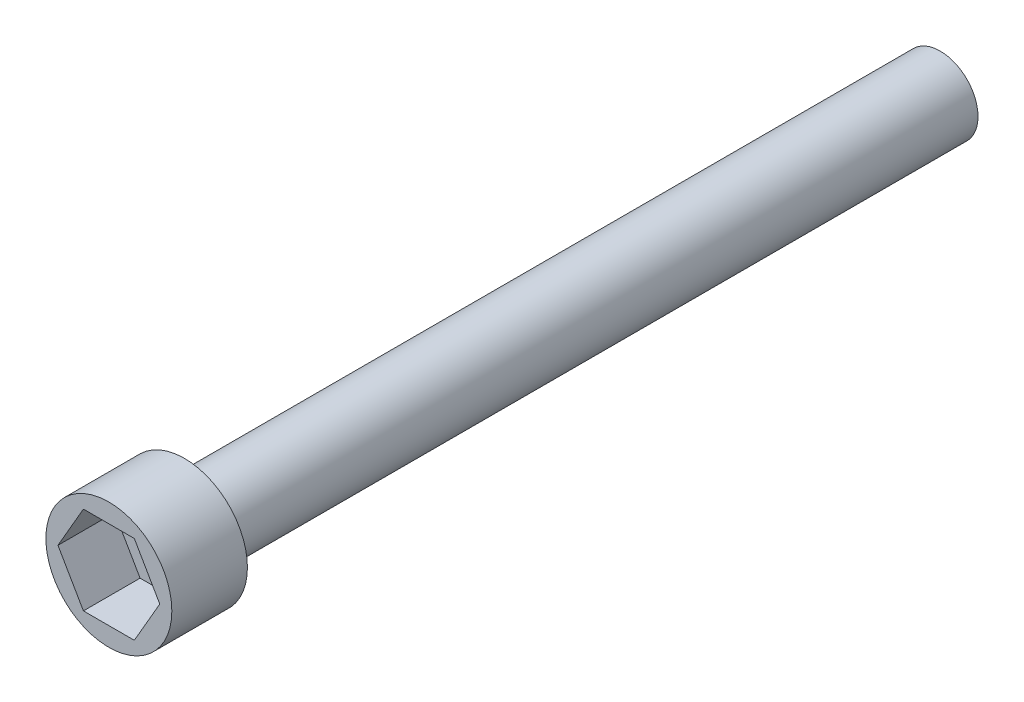
SolidWorks part; units mm, degrees
ref_plane "Plan de face" through (0, 0, 0) normal (0, 0, 1) x (1, 0, 0)
ref_plane "Plan de dessus" through (0, 0, 0) normal (0, 1, 0) x (1, 0, 0)
ref_plane "Plan de droite" through (0, 0, 0) normal (1, 0, 0) x (0, 0, -1)
sketch "Esquisse1" plane through (0, 0, 0) normal (0, 0, 1) x (1, 0, 0)
  circle A0 centre (0, 0) radius 3
  dimension "D1" = 6
extrude "Boss.-Extru.1" add sketch "Esquisse1" along normal blind 60
sketch "Esquisse2" plane through (0, 0, 60) normal (0, 0, 1) x (1, 0, 0)
  circle A0 centre (0, 0) radius 5
  dimension "D1" = 10
extrude "Boss.-Extru.2" add sketch "Esquisse2" along normal blind 6
sketch "Esquisse3" plane through (0, 0, 66) normal (0, 0, 1) x (1, 0, 0)
  line L1 (4.0415, 0) -> (2.0207, 3.5)
  line L2 (2.0207, 3.5) -> (-2.0207, 3.5)
  line L3 (-2.0207, 3.5) -> (-4.0415, 0)
  line L4 (-4.0415, 0) -> (-2.0207, -3.5)
  line L5 (-2.0207, -3.5) -> (2.0207, -3.5)
  line L6 (2.0207, -3.5) -> (4.0415, 0)
  circle A0 centre (0, 0) radius 3.5 construction
  dimension "D1" = 7
extrude "Enlèv. mat.-Extru.1" cut sketch "Esquisse3" against normal blind 4.5
